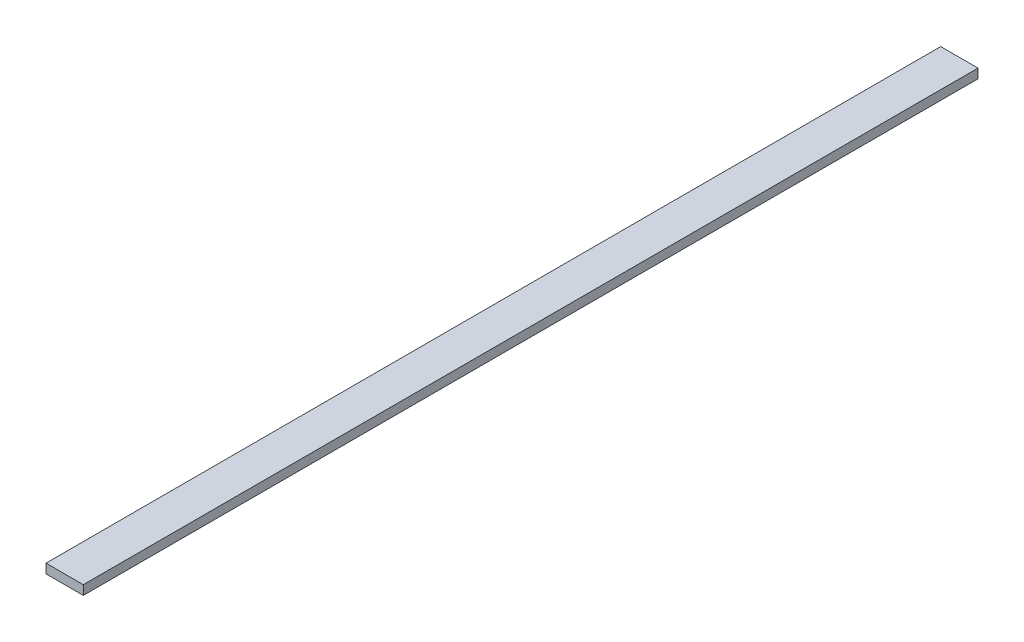
SolidWorks part; units mm, degrees
ref_plane "Front Plane" through (0, 0, 0) normal (0, 0, 1) x (1, 0, 0)
ref_plane "Top Plane" through (0, 0, 0) normal (0, 1, 0) x (1, 0, 0)
ref_plane "Right Plane" through (0, 0, 0) normal (1, 0, 0) x (0, 0, -1)
sketch "Sketch1" plane through (0, 0, 0) normal (0, 0, 1) x (1, 0, 0)
  line L0 (0, 3.175) -> (0, -3.175)
  line L1 (-12.7, 0) -> (12.7, 0) construction
  point P6 (0, 0)
  dimension "Width" = 25.4
  dimension "Thk" = 6.35
sketch "Sketch2" plane through (0, 0, 0) normal (1, 0, 0) x (0, 0, -1)
  line L0 (304.8, 0) -> (-304.8, 0)
  point P4 (0, 0)
  dimension "Length" = 609.6
sketch "Sketch3" plane through (0, 0, 0) normal (0, 0, 1) x (1, 0, 0)
  line L1 (12.7, 3.175) -> (-12.7, 3.175)
  line L2 (12.7, 3.175) -> (12.7, -3.175)
  line L3 (12.7, -3.175) -> (-12.7, -3.175)
  line L4 (-12.7, 3.175) -> (-12.7, -3.175)
  line L5 (12.7, 3.175) -> (-12.7, -3.175) construction
  line L6 (12.7, -3.175) -> (-12.7, 3.175) construction
  point P0 (0, 0)
extrude "Boss-Extrude1" add sketch "Sketch3" along normal up to vertex (304.8 mm away) and the other way up to vertex (304.8 mm away) up to point (0, 0, 304.8) other way up to point (0, 0, -304.8)
